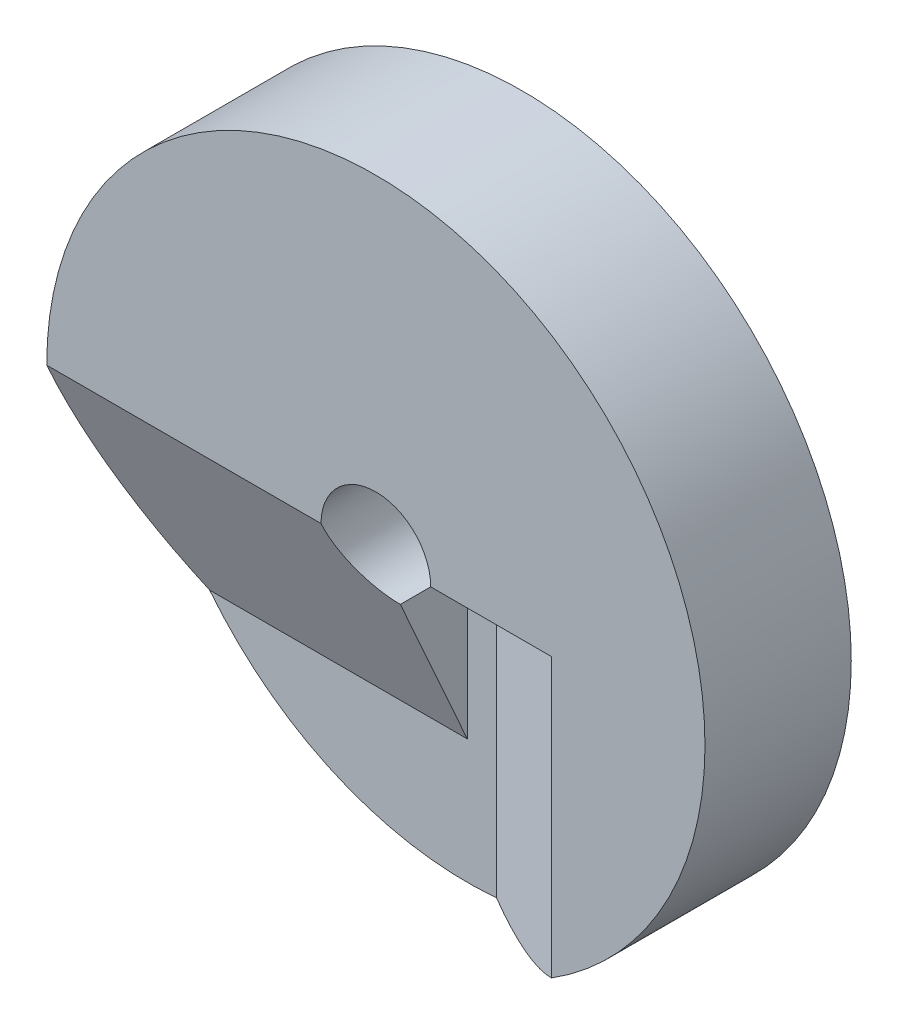
SolidWorks part; units mm, degrees
ref_plane "Alzado" through (0, 0, 0) normal (0, 0, 1) x (1, 0, 0)
ref_plane "Planta" through (0, 0, 0) normal (0, 1, 0) x (1, 0, 0)
ref_plane "Vista lateral" through (0, 0, 0) normal (1, 0, 0) x (0, 0, -1)
sketch "Croquis1" plane through (0, 0, 0) normal (0, 0, 1) x (1, 0, 0)
  circle A0 centre (0, 0) radius 9
  circle A1 centre (0, 0) radius 1.5
  dimension "D1" = 18
  dimension "D2" = 3
extrude "Saliente-Extruir1" add sketch "Croquis1" along normal blind 4
sketch "Croquis2" plane through (0, 0, 0) normal (1, 0, 0) x (0, 0, -1)
  line L3 (-4, -9) -> (0, -9) construction
  line L4 (-4, 9) -> (0, 9)
  line L5 (-4, 9) -> (-4, -9)
  line L6 (-4, -9) -> (0, -9)
  line L7 (0, 9) -> (0, -9)
  line L8 (-4, 0) -> (-1.5, -5.6)
  line L9 (-1.5, -5.6) -> (-1.5, -9)
  line L10 (0, -9) -> (0, 9) construction
  dimension "D1" = 1.5
  dimension "D2" = 3.4
extrude "Cortar-Extruir1" cut sketch "Croquis2" against normal blind 15 contours L9 L8 L5 L6
sketch "Croquis3" plane through (0, 0, 0) normal (0, 1, 0) x (1, 0, 0)
  line L0 (0, -4) -> (0, -3.3304) construction
  line L1 (0, -4) -> (0, -1.5)
  line L3 (-9, -4) -> (9, -4) construction
  line L4 (4.8035, -4) -> (0, -4)
  line L5 (-7.0456, -1.5) -> (0, -1.5) construction
  line L6 (-7.0456, -1.5) -> (0, -1.5)
  line L7 (0, -1.5) -> (0.7982, -1.5)
  line L8 (0.7982, -1.5) -> (4.8035, -4)
  point P0 (4.8035, -3)
extrude "Cortar-Extruir2" cut sketch "Croquis3" against normal blind 10
